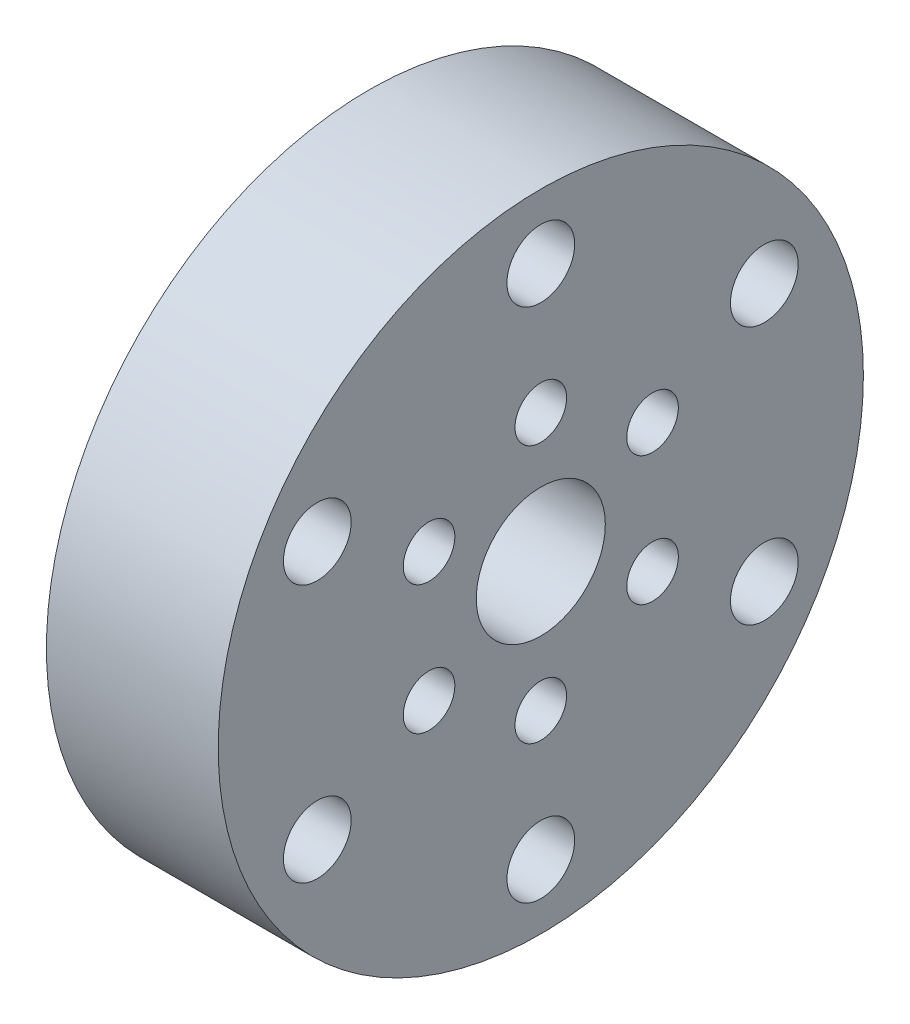
SolidWorks part; units mm, degrees
material "ABS"
ref_plane "前视基准面" through (0, 0, 0) normal (0, 0, 1) x (1, 0, 0)
ref_plane "上视基准面" through (0, 0, 0) normal (0, 1, 0) x (1, 0, 0)
ref_plane "右视基准面" through (0, 0, 0) normal (1, 0, 0) x (0, 0, -1)
other "Configuration Table"
sketch "草图1" plane through (0, 0, 0) normal (1, 0, 0) x (0, 0, -1)
  line L0 (0, 0) -> (0, 16) construction
  circle A0 centre (0, 0) radius 20
  circle A1 centre (0, 16) radius 2.1
  circle A2 centre (13.8564, 8) radius 2.1
  circle A3 centre (13.8564, -8) radius 2.1
  circle A4 centre (0, -16) radius 2.1
  circle A5 centre (-13.8564, -8) radius 2.1
  circle A6 centre (-13.8564, 8) radius 2.1
  circle A7 centre (0, 8) radius 1.6
  circle A8 centre (6.9282, 4) radius 1.6
  circle A9 centre (6.9282, -4) radius 1.6
  circle A10 centre (0, -8) radius 1.6
  circle A11 centre (-6.9282, -4) radius 1.6
  circle A12 centre (-6.9282, 4) radius 1.6
  circle A13 centre (0, 0) radius 4
  point P17 (0, 0)
  dimension "D1" = 40
  dimension "D2" = 4.2
  dimension "D5" = 3.2
  dimension "D6" = 8
  dimension "D7" = 8
  dimension "D3" = 16
  dimension "D4" = 6
extrude "凸台-拉伸1" add sketch "草图1" along normal blind 10.65
sketch "草图2" plane through (10.65, 0, 0) normal (1, 0, 0) x (0, 0, -1)
  line L0 (0, -20) -> (50, -20)
  line L1 (50, -20) -> (72.9431, -52.7661)
  line L2 (20, 0) -> (57.9698, 0)
  line L3 (57.9698, 0) -> (82.3133, -34.7661)
  line L4 (82.3133, -34.7661) -> (122.9431, -34.7661)
  line L5 (122.9431, -34.7661) -> (122.9431, -52.7661)
  line L6 (122.9431, -52.7661) -> (72.9431, -52.7661)
  line L7 (122.9431, -43.7661) -> (77.6282, -43.7661) construction
  line L8 (77.6282, -43.7661) -> (55.0336, -11.4977) construction
  line L9 (6.9001, 18.772) -> (57.9698, 0)
  circle A0 centre (0, 0) radius 20 construction
  circle A2 centre (116.9431, -43.7661) radius 2.1
  circle A3 centre (0, 0) radius 20
  circle A4 centre (0, 0) radius 20
  circle A5 centre (101.9431, -43.7661) radius 2.1
  circle A6 centre (86.9431, -43.7661) radius 2.1
  circle M14 centre (0, 0) radius 20
  dimension "D9" = 4.2
  dimension "D10" = 6
  dimension "D12" = 15
  dimension "D1" = 0
  dimension "D2" = 50
  dimension "D3" = 125
  dimension "D4" = 18
  dimension "D5" = 40
  dimension "D6" = 18
  dimension "D7" = 50
  dimension "D8" = 9
  dimension "D11" = 3
extrude "凸台-拉伸2" add sketch "草图2" against normal blind 4 contours L6 L5 L4 L3 L2 L0 L1 M14 | L9 L2 M14
fillet "圆角1" radius 3 6 edges at (8.65, -20, -50) (8.65, -52.7661, -72.9431) (8.65, -52.7661, -122.9431) (8.65, -34.7661, -122.9431) (8.65, -34.7661, -82.3133) (8.65, 0, -57.9698)
sketch "草图3" plane through (10.65, 0, 0) normal (1, 0, 0) x (0, 0, -1)
  line L2 (5.1751, 14.079) -> (55.3619, -4.3685)
  line L3 (17.5916, 9.515) -> (55.3619, -4.3685)
  line L4 (55.3619, -4.3685) -> (48.4383, -15)
  line L5 (0, -15) -> (48.4383, -15)
  line L6 (13.2288, -15) -> (48.4383, -15)
  line L7 (62.2003, -37.5883) -> (77.0223, -27.2098) construction
  line L8 (50.8958, -21.2793) -> (72.0473, -51.4868) construction
  line L9 (58.5093, -0.7705) -> (81.4175, -33.4868) construction
  line L10 (69.6113, -32.3991) -> (73.0528, -37.314) construction
  line L11 (71.3315, -31.1946) -> (74.773, -36.1095)
  line L12 (67.8911, -33.6036) -> (71.3326, -38.5185)
  line L13 (60.4341, -19.2926) -> (63.8755, -24.2076) construction
  line L14 (62.1543, -18.0881) -> (65.5958, -23.003)
  line L15 (58.7139, -20.4971) -> (62.1553, -25.4121)
  line L16 (42.12, 20.1465) -> (30.8335, -15)
  line L17 (39.7397, 20.9109) -> (27.2146, -18.0928)
  line L18 (44.5002, 19.3821) -> (33.2138, -15.7644)
  line L19 (39.7397, 20.9109) -> (28.4532, -14.2356) construction
  circle A0 centre (0, 0) radius 20
  arc A1 (71.3315, -31.1946) -> (67.8911, -33.6036) centre (69.6113, -32.3991) ccw
  arc A2 (71.3326, -38.5185) -> (74.773, -36.1095) centre (73.0528, -37.314) ccw
  arc A3 (62.1543, -18.0881) -> (58.7139, -20.4971) centre (60.4341, -19.2926) ccw
  arc A4 (62.1553, -25.4121) -> (65.5958, -23.003) centre (63.8755, -24.2076) ccw
  point P15 (71.332, -34.8565)
  point P24 (62.1548, -21.7501)
  point P32 (36.4767, 2.5733)
  dimension "D1" = 5
  dimension "D3" = 40
  dimension "D4" = 2.1
  dimension "D5" = 6
  dimension "D7" = 2.5
  dimension "D2" = 5
  dimension "D8" = 2.5
  dimension "D6" = 2
extrude "切除-拉伸1" cut sketch "草图3" against normal blind 4 contours A0 L6 L17 L3 | L3 L18 L6 L4 | L15 A4 L14 A3 | L12 A2 L11 A1
fillet "圆角2" radius 4 8 edges at (8.65, -4.3685, -55.3619) (8.65, -15, -48.4383) (8.65, -15, -33.4593) (8.65, 1.71, -38.8253) (8.65, 9.515, -17.5916) (8.65, 3.4365, -34.1282) (8.65, -15, -28.2078) (8.65, -15, -13.2288)
sketch "草图4" plane through (10.65, 0, 0) normal (1, 0, 0) x (0, 0, -1)
  line L0 (58.5093, -0.7705) -> (81.4175, -33.4868) construction
  circle A0 centre (58.5788, -9.5869) radius 2.15
  dimension "D1" = 4.3
  dimension "D2" = 5
extrude "切除-拉伸2" cut sketch "草图4" against normal blind 4
sketch "Sketch1" plane through (10.65, 0, 0) normal (1, 0, 0) x (0, 0, -1)
  line L7 (81.4175, -33.4868) -> (58.5093, -0.7705)
  line L8 (57.0869, 0.3245) -> (6.9001, 18.772)
  line L9 (0, -20) -> (48.4383, -20)
  line L10 (50.8958, -21.2793) -> (72.0473, -51.4868)
  line L11 (74.5048, -52.7661) -> (119.9431, -52.7661)
  line L12 (122.9431, -49.7661) -> (122.9431, -37.7661)
  line L13 (119.9431, -34.7661) -> (83.875, -34.7661)
  line L14 (81.4175, -33.4868) -> (58.5093, -0.7705)
  line L15 (57.0869, 0.3245) -> (6.9001, 18.772)
  line L16 (0, -20) -> (48.4383, -20)
  line L17 (50.8958, -21.2793) -> (72.0473, -51.4868)
  line L18 (74.5048, -52.7661) -> (119.9431, -52.7661)
  line L19 (122.9431, -49.7661) -> (122.9431, -37.7661)
  line L20 (119.9431, -34.7661) -> (83.875, -34.7661)
  circle A0 centre (0, 0) radius 20
  arc A1 (6.9001, 18.772) -> (0, -20) centre (0, 0) ccw construction
  arc A8 (58.5093, -0.7705) -> (57.0869, 0.3245) centre (56.0519, -2.4913) ccw
  arc A9 (6.9001, 18.772) -> (0, -20) centre (0, 0) ccw
  arc A10 (50.8958, -21.2793) -> (48.4383, -20) centre (48.4383, -23) ccw
  arc A11 (72.0473, -51.4868) -> (74.5048, -52.7661) centre (74.5048, -49.7661) ccw
  arc A12 (119.9431, -52.7661) -> (122.9431, -49.7661) centre (119.9431, -49.7661) ccw
  arc A13 (122.9431, -37.7661) -> (119.9431, -34.7661) centre (119.9431, -37.7661) ccw
  arc A14 (81.4175, -33.4868) -> (83.875, -34.7661) centre (83.875, -31.7661) ccw
  arc A15 (58.5093, -0.7705) -> (57.0869, 0.3245) centre (56.0519, -2.4913) ccw
  arc A16 (6.9001, 18.772) -> (0, -20) centre (0, 0) ccw
  arc A17 (50.8958, -21.2793) -> (48.4383, -20) centre (48.4383, -23) ccw
  arc A18 (72.0473, -51.4868) -> (74.5048, -52.7661) centre (74.5048, -49.7661) ccw
  arc A19 (119.9431, -52.7661) -> (122.9431, -49.7661) centre (119.9431, -49.7661) ccw
  arc A20 (122.9431, -37.7661) -> (119.9431, -34.7661) centre (119.9431, -37.7661) ccw
  arc A21 (81.4175, -33.4868) -> (83.875, -34.7661) centre (83.875, -31.7661) ccw
  dimension "D1" = 0
extrude "Cut-Extrude1" cut sketch "Sketch1" against normal blind 10 contours A21 L14 A15 L15 A0 L16 A17 L17 A18 L18 A19 L19 A20 L20
